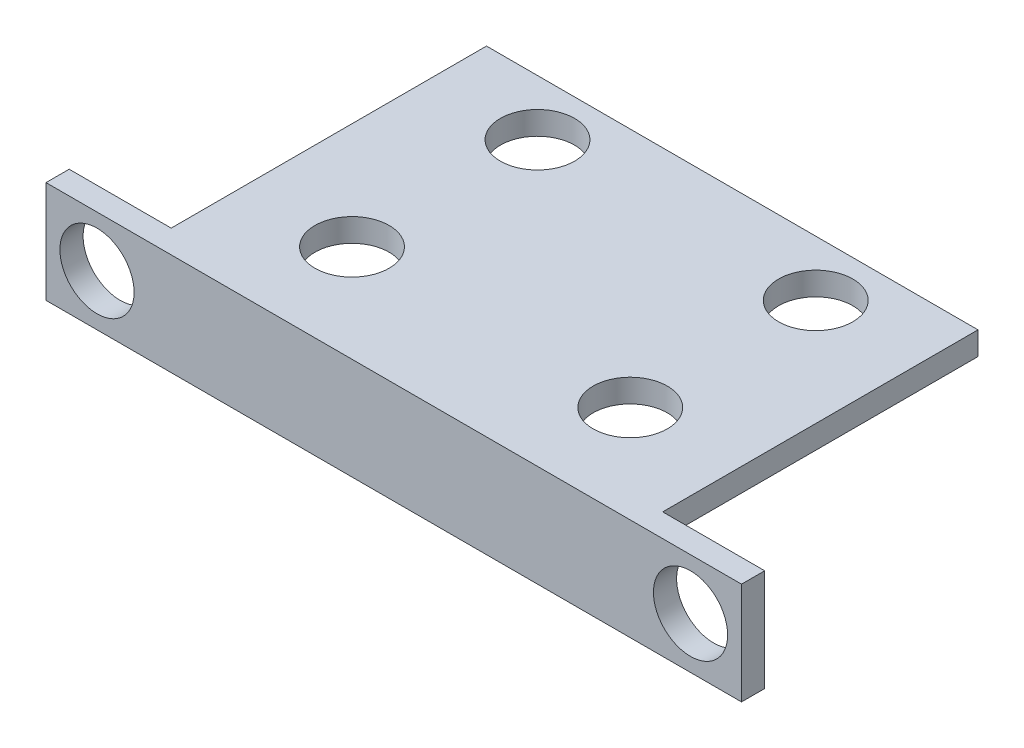
SolidWorks part; units mm, degrees
ref_plane "前视基准面" through (0, 0, 0) normal (0, 0, 1) x (1, 0, 0)
ref_plane "上视基准面" through (0, 0, 0) normal (0, 1, 0) x (1, 0, 0)
ref_plane "右视基准面" through (0, 0, 0) normal (1, 0, 0) x (0, 0, -1)
sketch "草图1" plane through (0, 0, 0) normal (0, 1, 0) x (1, 0, 0)
  line L0 (13.8862, -19.4271) -> (13.8862, -8.9271) construction
  line L1 (-12.6138, 17.0729) -> (40.3862, 17.0729)
  line L2 (-12.6138, 17.0729) -> (-12.6138, -19.4271)
  line L3 (-12.6138, -19.4271) -> (40.3862, -19.4271)
  line L4 (40.3862, 17.0729) -> (40.3862, -19.4271)
  line L5 (13.8862, -8.9271) -> (13.8862, 11.0729) construction
  line L6 (13.8862, 11.0729) -> (28.8862, 11.0729) construction
  line L7 (13.8862, 11.0729) -> (-1.1138, 11.0729) construction
  line L8 (13.8862, -8.9271) -> (-1.1138, -8.9271) construction
  line L9 (13.8862, -8.9271) -> (28.8862, -8.9271) construction
  circle A0 centre (-1.1138, 11.0729) radius 4
  circle A1 centre (28.8862, 11.0729) radius 4
  circle A2 centre (28.8862, -8.9271) radius 4
  circle A3 centre (-1.1138, -8.9271) radius 4
  dimension "D6" = 8
  dimension "D7" = 8
  dimension "D8" = 8
  dimension "D9" = 8
  dimension "D1" = 36.5
  dimension "D2" = 53
  dimension "D3" = 15
  dimension "D4" = 20
  dimension "D5" = 10.5
extrude "凸台-拉伸1" add sketch "草图1" along normal blind 2.5
sketch "草图2" plane through (0, 0, 19.4271) normal (0, 0, 1) x (1, 0, 0)
  line L0 (-18.1138, -3) -> (-18.1138, 2.5) construction
  line L1 (51.3862, 2.5) -> (-23.6138, 2.5)
  line L2 (51.3862, 2.5) -> (51.3862, -8.5)
  line L3 (51.3862, -8.5) -> (-23.6138, -8.5)
  line L4 (-23.6138, 2.5) -> (-23.6138, -8.5)
  line L5 (-12.6138, 2.5) -> (40.3862, 2.5) construction
  line L6 (-12.6138, 0) -> (-12.6138, -8.5) construction
  line L7 (-18.1138, -3) -> (-23.6138, -3) construction
  line L8 (40.3862, 0) -> (40.3862, -8.5) construction
  line L9 (45.8862, -3) -> (51.3862, -3) construction
  line L10 (45.8862, -3) -> (45.8862, 2.5) construction
  circle A0 centre (-18.1138, -3) radius 4
  circle A1 centre (45.8862, -3) radius 4
  point P6 (13.8862, 2.5)
  point P10 (13.8862, 2.5)
  dimension "D4" = 8
  dimension "D6" = 8
  dimension "D1" = 11
  dimension "D2" = 75
  dimension "D3" = 5.5
  dimension "D5" = 5.5
  dimension "D7" = 5.5
  dimension "D8" = 5.5
extrude "凸台-拉伸2" add sketch "草图2" against normal blind 2.5
